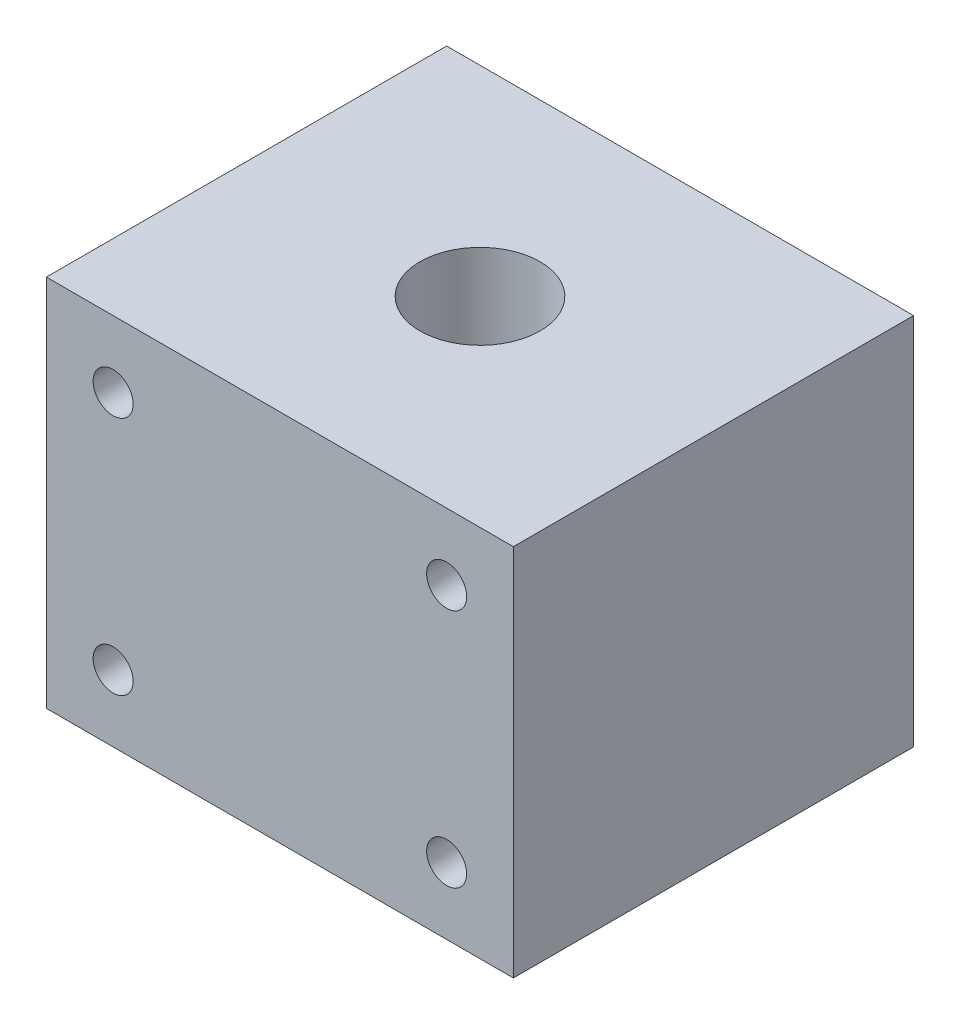
SolidWorks part; units mm, degrees
ref_plane "Front Plane" through (0, 0, 0) normal (0, 0, 1) x (1, 0, 0)
ref_plane "Top Plane" through (0, 0, 0) normal (0, 1, 0) x (1, 0, 0)
ref_plane "Right Plane" through (0, 0, 0) normal (1, 0, 0) x (0, 0, -1)
sketch "Sketch1" plane through (0, 0, 0) normal (0, 1, 0) x (1, 0, 0)
  line L1 (-17.5, -15) -> (17.5, -15)
  line L2 (-17.5, -15) -> (-17.5, 15)
  line L3 (-17.5, 15) -> (17.5, 15)
  line L4 (17.5, -15) -> (17.5, 15)
  line L5 (-17.5, -15) -> (17.5, 15) construction
  line L6 (-17.5, 15) -> (17.5, -15) construction
  point P0 (0, 0)
  dimension "D1" = 35
  dimension "D2" = 30
extrude "Boss-Extrude1" add sketch "Sketch1" along normal blind 28
sketch "Sketch2" plane through (0, 0, 15) normal (0, 0, 1) x (1, 0, 0)
  line L0 (-17.5, 28) -> (17.5, 28) construction
  line L1 (-17.5, 28) -> (-17.5, 0) construction
  line L2 (17.5, 28) -> (17.5, 0) construction
  line L3 (-17.5, 0) -> (17.5, 0) construction
  circle A0 centre (-12.5, 23) radius 1.5
  circle A1 centre (12.5, 23) radius 1.5
  circle A2 centre (12.5, 5) radius 1.5
  circle A3 centre (-12.5, 5) radius 1.5
  dimension "D1" = 3
  dimension "D4" = 5
  dimension "D2" = 5
  dimension "D3" = 5
  dimension "D5" = 5
  dimension "D6" = 5
  dimension "D7" = 5
  dimension "D8" = 5
  dimension "D9" = 5
extrude "Cut-Extrude1" cut sketch "Sketch2" against normal blind 10
sketch "Sketch5" plane through (0, 0, 0) normal (0, -1, 0) x (1, 0, 0)
  circle A0 centre (0, 0) radius 11.5
  dimension "D1" = 23
extrude "Cut-Extrude4" cut sketch "Sketch5" against normal blind 3
sketch "Sketch6" plane through (0, 3, 0) normal (0, -1, 0) x (-1, 0, 0)
  circle A0 centre (0, 0) radius 4.5
  dimension "9" = 9
extrude "Cut-Extrude5" cut sketch "Sketch6" along normal through all both and the other way through all
